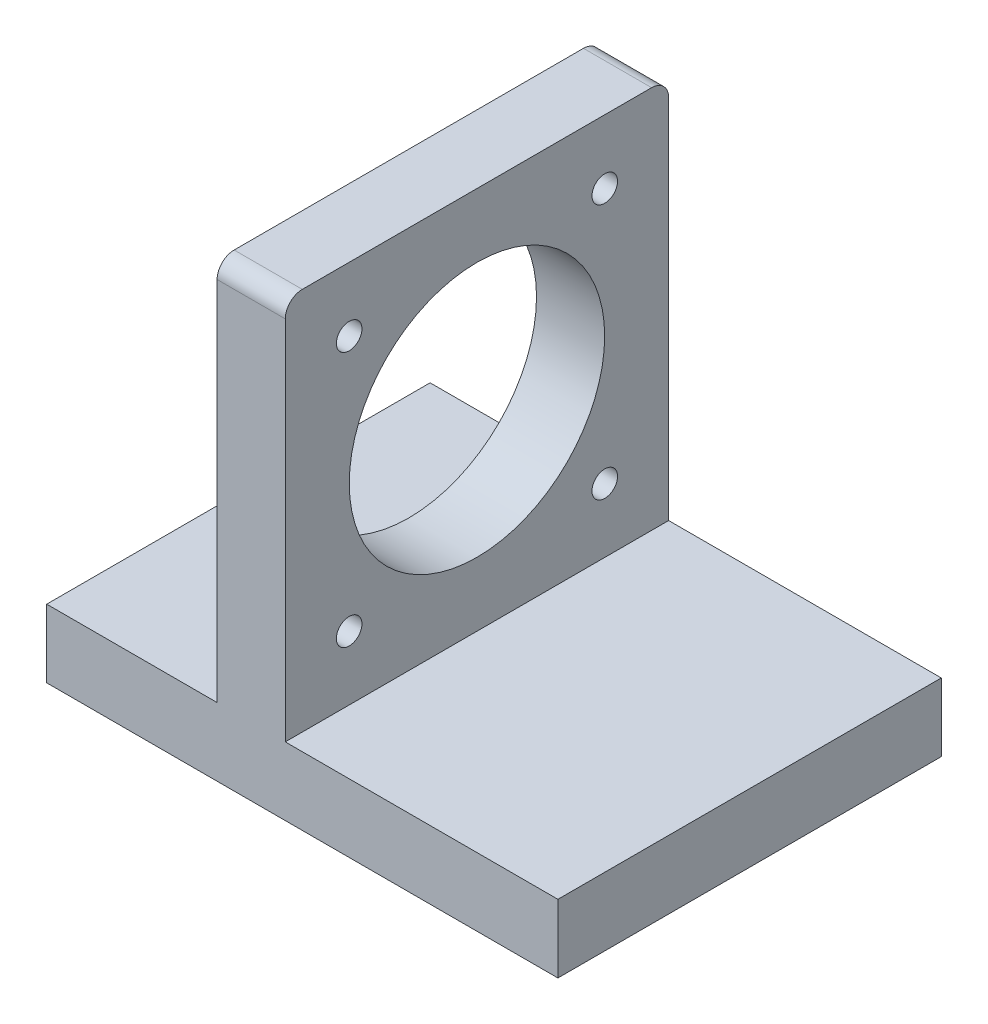
SolidWorks part; units mm, degrees
ref_plane "Front Plane" through (0, 0, 0) normal (0, 0, 1) x (1, 0, 0)
ref_plane "Top Plane" through (0, 0, 0) normal (0, 1, 0) x (1, 0, 0)
ref_plane "Right Plane" through (0, 0, 0) normal (1, 0, 0) x (0, 0, -1)
sketch "Sketch1" plane through (0, 0, 0) normal (0, 1, 0) x (1, 0, 0)
  line L1 (-30, 22.5) -> (30, 22.5)
  line L2 (-30, 22.5) -> (-30, -22.5)
  line L3 (-30, -22.5) -> (30, -22.5)
  line L4 (30, 22.5) -> (30, -22.5)
  line L5 (-30, 22.5) -> (30, -22.5) construction
  line L6 (-30, -22.5) -> (30, 22.5) construction
  point P0 (0, 0)
  dimension "D1" = 60
  dimension "D2" = 45
extrude "Boss-Extrude1" add sketch "Sketch1" along normal blind 8
sketch "Sketch2" plane through (0, 0, 0) normal (0, -1, 0) x (1, 0, 0)
  line L0 (-30, 0) -> (30, 0) construction
  line L1 (-30, -22.5) -> (-30, 22.5) construction
  line L2 (30, 22.5) -> (30, -22.5) construction
  line L3 (-20, 22.5) -> (-20, -22.5) construction
  line L4 (-30, 22.5) -> (30, 22.5) construction
  line L5 (30, -22.5) -> (-30, -22.5) construction
  circle A0 centre (-20, 14.5) radius 5
  circle A1 centre (-20, -14.5) radius 5
  dimension "D4" = 10
  dimension "D1" = 10
  dimension "D2" = 8
  dimension "D3" = 8
extrude "Cut-Extrude1" cut sketch "Sketch2" against normal blind 5
sketch "Sketch3" plane through (0, 0, 0) normal (0, -1, 0) x (1, 0, 0)
  line L0 (-10, 22.5) -> (-10, -22.5) construction
  line L1 (-30, 22.5) -> (30, 22.5) construction
  line L2 (30, -22.5) -> (-30, -22.5) construction
  line L4 (-10, 20) -> (10, 20)
  line L5 (-10, 20) -> (-10, -20)
  line L6 (-10, -20) -> (10, -20)
  line L7 (10, 20) -> (10, -20)
  dimension "D1" = 20
  dimension "D2" = 2.5
  dimension "D3" = 40
  dimension "D4" = 20
extrude "Cut-Extrude2" cut sketch "Sketch3" against normal blind 5
sketch "Sketch4" plane through (0, 8, 0) normal (0, 1, 0) x (1, 0, 0)
  line L0 (-10, 22.5) -> (-10, -22.5) construction
  line L1 (30, 22.5) -> (-30, 22.5) construction
  line L2 (-30, -22.5) -> (30, -22.5) construction
  line L4 (-10, -22.5) -> (-2, -22.5)
  line L5 (-10, -22.5) -> (-10, 22.5)
  line L6 (-10, 22.5) -> (-2, 22.5)
  line L7 (-2, -22.5) -> (-2, 22.5)
  dimension "D1" = 20
  dimension "D2" = 8
extrude "Boss-Extrude3" add sketch "Sketch4" along normal blind 45
sketch "Sketch6" plane through (-10, 0, 0) normal (-1, 0, 0) x (0, 0, 1)
  line L0 (-22.5, 53) -> (22.5, 8) construction
  line L2 (-15, 45.5) -> (15, 45.5)
  line L3 (-15, 45.5) -> (-15, 15.5)
  line L4 (-15, 15.5) -> (15, 15.5)
  line L5 (15, 45.5) -> (15, 15.5)
  line L6 (-15, 45.5) -> (15, 15.5) construction
  line L7 (-15, 15.5) -> (15, 45.5) construction
  circle A0 centre (-15, 45.5) radius 1.5
  circle A1 centre (15, 45.5) radius 1.5
  circle A2 centre (15, 15.5) radius 1.5
  circle A3 centre (-15, 15.5) radius 1.5
  point P4 (0, 30.5)
  dimension "D2" = 3
  dimension "D1" = 30
extrude "Cut-Extrude3" cut sketch "Sketch6" against normal blind 45 contours A0 | A1 | A2 | A3
fillet "Fillet2" radius 2 2 edges at (-6, 53, -22.5) (-6, 53, 22.5)
sketch "Sketch7" plane through (-10, 0, 0) normal (-1, 0, 0) x (0, 0, 1)
  line L0 (-15, 45.5) -> (15, 15.5) construction
  line L1 (-15, 45.5) -> (15, 45.5)
  line L2 (-15, 45.5) -> (-15, 15.5)
  line L3 (-15, 15.5) -> (15, 15.5)
  line L4 (15, 45.5) -> (15, 15.5)
  circle A0 centre (0, 30.5) radius 14.9902
extrude "Cut-Extrude4" cut sketch "Sketch7" against normal through all contours A0
